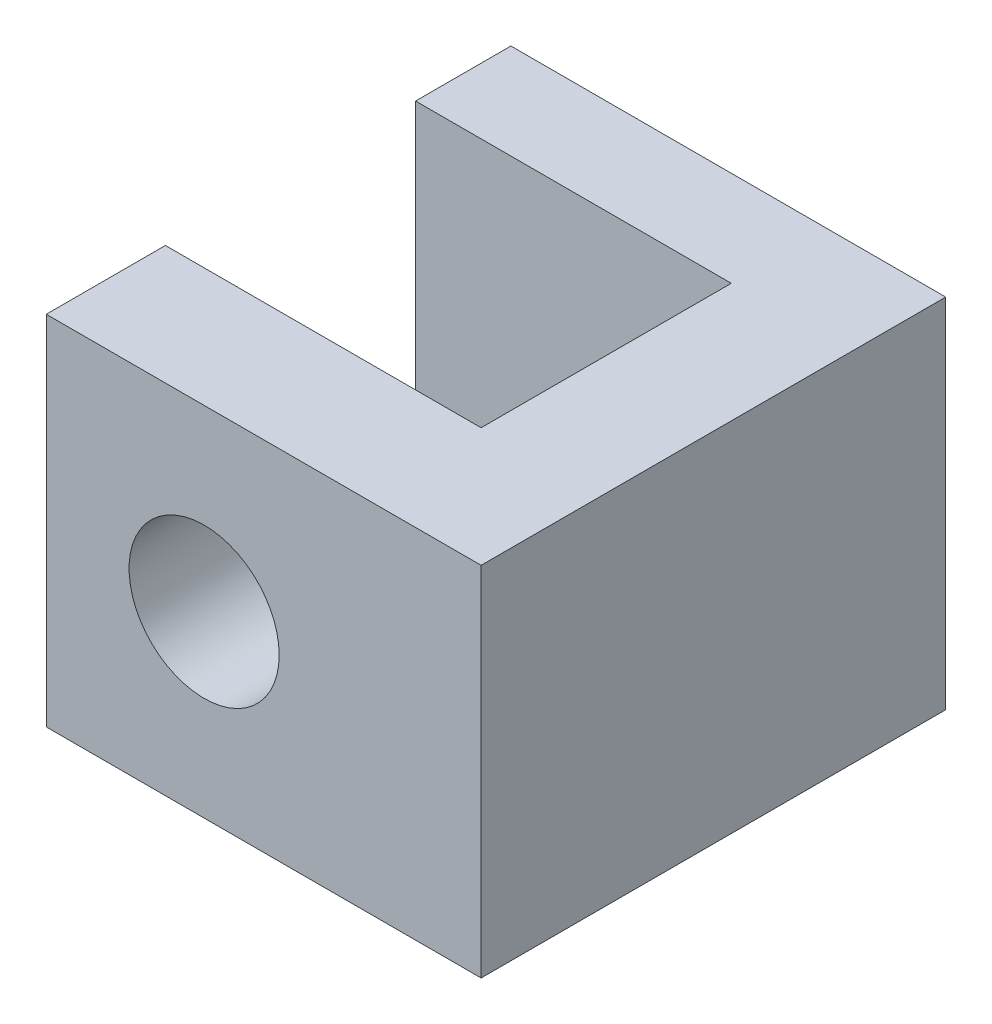
SolidWorks part; units mm, degrees
ref_plane "Front Plane" through (0, 0, 0) normal (0, 0, 1) x (1, 0, 0)
ref_plane "Top Plane" through (0, 0, 0) normal (0, 1, 0) x (1, 0, 0)
ref_plane "Right Plane" through (0, 0, 0) normal (1, 0, 0) x (0, 0, -1)
sketch "Sketch1" plane through (0, 0, 0) normal (0, 1, 0) x (1, 0, 0)
  line L0 (-0.75, 0) -> (17.5, 0)
  line L1 (17.5, 0) -> (17.5, 19.5)
  line L2 (17.5, 19.5) -> (-0.75, 19.5)
  line L4 (-0.75, 15.5) -> (12.5, 15.5)
  line L5 (12.5, 15.5) -> (12.5, 5)
  line L6 (12.5, 5) -> (6.25, 5)
  line L9 (6.25, 5) -> (-0.75, 5)
  line L10 (-0.75, 5) -> (-0.75, 0)
  line L12 (-0.75, 15.5) -> (-0.75, 19.5)
  dimension "D1" = 7
  dimension "D2" = 10.5
extrude "Boss-Extrude2" add sketch "Sketch1" along normal mid plane 15
sketch "Sketch6" plane through (0, 0, 0) normal (0, 0, 1) x (1, 0, 0)
  circle A0 centre (5.875, 0) radius 3.15
  dimension "D1" = 6.3
extrude "Cut-Extrude1" cut sketch "Sketch6" against normal blind 10
sketch "Sketch8" plane through (0, 0, -19.5) normal (0, 0, -1) x (-1, 0, 0)
  circle A0 centre (-5.875, 0) radius 2.95
  dimension "D1" = 5.9
extrude "Boss-Extrude3" add sketch "Sketch8" along normal blind 2.9
